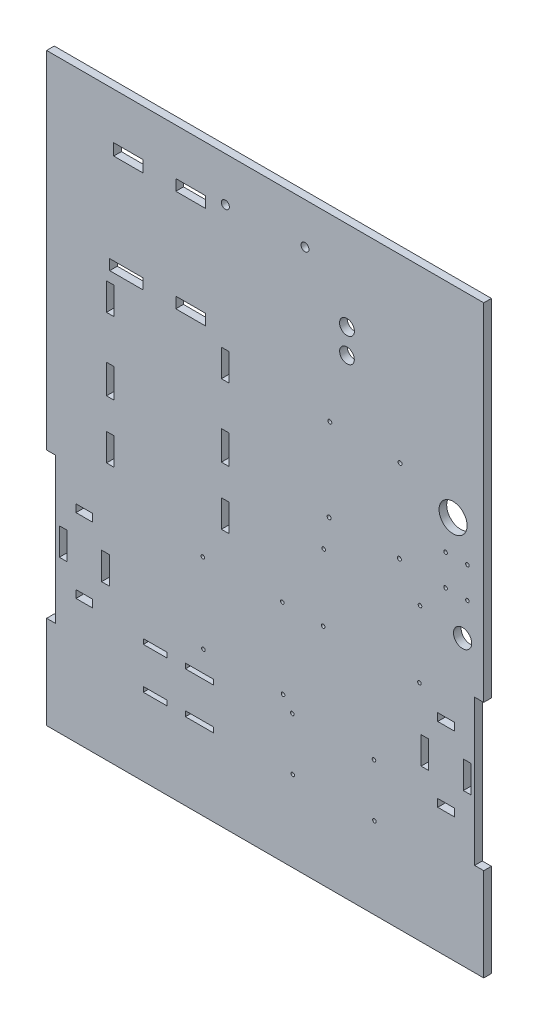
SolidWorks part; units mm, degrees
ref_plane "Front Plane" through (0, 0, 0) normal (0, 0, 1) x (1, 0, 0)
ref_plane "Top Plane" through (0, 0, 0) normal (0, 1, 0) x (1, 0, 0)
ref_plane "Right Plane" through (0, 0, 0) normal (1, 0, 0) x (0, 0, -1)
sketch "Sketch1" plane through (0, 0, 0) normal (0, 0, 1) x (1, 0, 0)
  line L1 (-152.4, 152.4) -> (152.4, 152.4)
  line L2 (-152.4, 152.4) -> (-152.4, -152.4)
  line L3 (-152.4, -152.4) -> (152.4, -152.4)
  line L4 (152.4, 152.4) -> (152.4, -152.4)
  line L5 (-152.4, 152.4) -> (152.4, -152.4) construction
  line L6 (-152.4, -152.4) -> (152.4, 152.4) construction
  point P0 (0, 0)
  dimension "D1" = 304.8
  dimension "D2" = 304.8
extrude "Boss-Extrude1" add sketch "Sketch1" along normal blind 5.334
sketch "Sketch2" plane through (0, 0, 0) normal (0, 0, -1) x (-1, 0, 0)
  line L0 (152.4, 152.4) -> (152.4, -152.4) construction
  line L1 (152.4, -12.7) -> (146.05, -12.7)
  line L2 (152.4, -12.7) -> (152.4, -114.3)
  line L3 (152.4, -114.3) -> (146.05, -114.3)
  line L4 (146.05, -12.7) -> (146.05, -114.3)
  line L5 (-152.4, -152.4) -> (-152.4, 152.4) construction
  line L6 (-152.4, -12.7) -> (-146.05, -12.7)
  line L7 (-152.4, -12.7) -> (-152.4, -114.3)
  line L8 (-152.4, -114.3) -> (-146.05, -114.3)
  line L9 (-146.05, -12.7) -> (-146.05, -114.3)
  line L10 (152.4, -152.4) -> (-152.4, -152.4) construction
  dimension "D1" = 101.6
  dimension "D2" = 101.6
  dimension "D3" = 38.1
  dimension "D4" = 38.1
  dimension "D5" = 6.35
  dimension "D6" = 6.35
extrude "Cut-Extrude1" cut sketch "Sketch2" against normal through all
sketch "Sketch26" plane through (0, 0, 5.334) normal (0, 0, 1) x (1, 0, 0)
  line L1 (-131.9107, -92.075) -> (-120.3113, -92.075)
  line L2 (-131.9107, -92.075) -> (-131.9107, -86.741)
  line L3 (-131.9107, -86.741) -> (-120.3113, -86.741)
  line L4 (-120.3113, -92.075) -> (-120.3113, -86.741)
  line L5 (-114.046, -73.025) -> (-108.712, -73.025)
  line L6 (-114.046, -73.025) -> (-114.046, -53.975)
  line L7 (-114.046, -53.975) -> (-108.712, -53.975)
  line L8 (-108.712, -73.025) -> (-108.712, -53.975)
  line L9 (-131.9107, -40.259) -> (-120.3113, -40.259)
  line L10 (-131.9107, -40.259) -> (-131.9107, -34.925)
  line L11 (-131.9107, -34.925) -> (-120.3113, -34.925)
  line L12 (-120.3113, -40.259) -> (-120.3113, -34.925)
  line L13 (-143.51, -73.025) -> (-138.176, -73.025)
  line L14 (-143.51, -73.025) -> (-143.51, -53.975)
  line L15 (-143.51, -53.975) -> (-138.176, -53.975)
  line L16 (-138.176, -73.025) -> (-138.176, -53.975)
extrude "Cut-Extrude11" cut sketch "Sketch26" against normal through all
sketch "Sketch27" plane through (0, 0, 5.334) normal (0, 0, 1) x (1, 0, 0)
  line L1 (131.9107, -92.075) -> (120.3113, -92.075)
  line L2 (131.9107, -92.075) -> (131.9107, -86.741)
  line L3 (131.9107, -86.741) -> (120.3113, -86.741)
  line L4 (120.3113, -92.075) -> (120.3113, -86.741)
  line L5 (114.046, -73.025) -> (108.712, -73.025)
  line L6 (114.046, -73.025) -> (114.046, -53.975)
  line L7 (114.046, -53.975) -> (108.712, -53.975)
  line L8 (108.712, -73.025) -> (108.712, -53.975)
  line L9 (131.9107, -40.259) -> (120.3113, -40.259)
  line L10 (131.9107, -40.259) -> (131.9107, -34.925)
  line L11 (131.9107, -34.925) -> (120.3113, -34.925)
  line L12 (120.3113, -40.259) -> (120.3113, -34.925)
  line L13 (143.51, -73.025) -> (138.176, -73.025)
  line L14 (143.51, -73.025) -> (143.51, -53.975)
  line L15 (143.51, -53.975) -> (138.176, -53.975)
  line L16 (138.176, -73.025) -> (138.176, -53.975)
extrude "Cut-Extrude12" cut sketch "Sketch27" against normal through all
sketch "Sketch29" plane through (0, 0, 0) normal (0, 0, -1) x (-1, 0, 0)
  line L0 (152.4, -114.3) -> (152.4, -152.4) construction
  line L1 (-152.4, -152.4) -> (152.4, -152.4)
  line L2 (-152.4, -152.4) -> (-152.4, -128.3152)
  line L3 (-152.4, -128.3152) -> (152.4, -128.3152)
  line L4 (152.4, -152.4) -> (152.4, -128.3152)
extrude "Cut-Extrude13" cut sketch "Sketch29" against normal through all
sketch "Sketch30" plane through (0, 0, 0) normal (0, 0, -1) x (-1, 0, 0)
  circle A0 centre (27.7607, 197.7649) radius 2.7781
  circle A1 centre (-27.7607, 199.9013) radius 2.7781
sketch "Sketch31" plane through (0, 0, 0) normal (0, 0, -1) x (-1, 0, 0)
  circle A0 centre (-94.0723, 102.6888) radius 1.375
  circle A1 centre (-45.0742, 103.1164) radius 1.375
  circle A2 centre (-93.5662, 44.691) radius 1.375
  circle A3 centre (-44.5681, 45.1186) radius 1.375
extrude "Cut-Extrude15" cut sketch "Sketch31" against normal through all
sketch "Sketch32" plane through (0, 0, 0) normal (0, 0, -1) x (-1, 0, 0)
  circle A0 centre (-125.7819, 64.7185) radius 1.25
  circle A1 centre (-141.0219, 64.7185) radius 1.25
  circle A2 centre (-141.0219, 43.1285) radius 1.25
  circle A3 centre (-125.7819, 43.1285) radius 1.25
extrude "Cut-Extrude16" cut sketch "Sketch32" against normal through all
sketch "Sketch34" plane through (0, 0, 0) normal (0, 0, -1) x (-1, 0, 0)
  circle A0 centre (-75.859, -85.6615) radius 1.2492
  circle A1 centre (-76.1788, -122.3001) radius 1.25
  circle A2 centre (-19.2207, -122.7972) radius 1.2525
  circle A3 centre (-18.9009, -86.1585) radius 1.252
extrude "Cut-Extrude18" cut sketch "Sketch34" against normal through all
sketch "Sketch38" plane through (0, 0, 0) normal (0, 0, -1) x (-1, 0, 0)
  circle A0 centre (43.525, -22.8195) radius 1.2482
  circle A1 centre (-11.9729, -22.3352) radius 1.2536
  circle A2 centre (-12.4572, -77.8331) radius 1.2525
  circle A3 centre (43.0406, -78.3174) radius 1.2379
extrude "Cut-Extrude22" cut sketch "Sketch38" against normal through all
sketch "Sketch40" plane through (0, 152.4, 0) normal (0, 1, 0) x (1, 0, 0)
  line L1 (152.4, -5.334) -> (-152.4, -5.334)
  line L2 (152.4, -5.334) -> (152.4, 0)
  line L3 (152.4, 0) -> (-152.4, 0)
  line L4 (-152.4, -5.334) -> (-152.4, 0)
extrude "Boss-Extrude2" add sketch "Sketch40" along normal blind 76.2
sketch "Sketch41" plane through (0, 0, 0) normal (0, 0, -1) x (-1, 0, 0)
  circle A1 centre (-27.7607, 199.9013) radius 2.7781
  circle A2 centre (27.7607, 197.7649) radius 2.7781
extrude "Cut-Extrude24" cut sketch "Sketch41" against normal through all
sketch "Sketch42" plane through (0, 0, 0) normal (0, 0, -1) x (-1, 0, 0)
  circle A0 centre (-40.4289, -22.6525) radius 1.2465
  circle A1 centre (-107.5463, -23.2383) radius 1.2519
  circle A2 centre (-107.9547, 23.56) radius 1.2487
  circle A3 centre (-40.8373, 24.1457) radius 1.2456
extrude "Cut-Extrude25" cut sketch "Sketch42" against normal through all and the other way through all
sketch "Sketch44" plane through (0, 0, 0) normal (0, 0, -1) x (-1, 0, 0)
  line L0 (8.1367, -121.7414) -> (109.7367, -121.7414) construction
  line L1 (84.9513, -121.7414) -> (68.4744, -121.7414)
  line L2 (84.9513, -121.7414) -> (84.9513, -125.2414)
  line L3 (84.9513, -125.2414) -> (68.4744, -125.2414)
  line L4 (68.4744, -121.7414) -> (68.4744, -125.2414)
  line L5 (8.1367, -96.3414) -> (109.7367, -96.3414) construction
  line L6 (84.9513, -96.3414) -> (68.4744, -96.3414)
  line L7 (84.9513, -96.3414) -> (84.9513, -92.8414)
  line L8 (84.9513, -92.8414) -> (68.4744, -92.8414)
  line L9 (68.4744, -96.3414) -> (68.4744, -92.8414)
  line L10 (55.5989, -121.7414) -> (55.5989, -96.3414) construction
  line L11 (55.5989, -121.7414) -> (35.9657, -121.7414)
  line L12 (55.5989, -121.7414) -> (55.5989, -125.3381)
  line L13 (55.5989, -125.3381) -> (35.9657, -125.3381)
  line L14 (35.9657, -121.7414) -> (35.9657, -125.3381)
  line L15 (55.5989, -96.4381) -> (35.9657, -96.4381)
  line L16 (55.5989, -96.4381) -> (55.5989, -92.9381)
  line L17 (55.5989, -92.9381) -> (35.9657, -92.9381)
  line L18 (35.9657, -96.4381) -> (35.9657, -92.9381)
  dimension "D1" = 3.5
  dimension "D2" = 3.5
extrude "Cut-Extrude27" cut sketch "Sketch44" against normal through all
sketch "Sketch45" plane through (0, 0, 0) normal (0, 0, -1) x (-1, 0, 0)
  line L0 (146.4593, 187.8495) -> (-21.8093, 189.318) construction
  line L1 (105.6204, 188.2059) -> (85.2662, 188.2059)
  line L2 (105.6204, 188.2059) -> (105.6204, 196.272)
  line L3 (105.6204, 196.272) -> (85.2662, 196.272)
  line L4 (85.2662, 188.2059) -> (85.2662, 196.272)
  line L5 (145.9051, 124.3519) -> (-22.3635, 125.8204) construction
  line L6 (62.325, 188.5838) -> (41.77, 188.5838)
  line L7 (62.325, 188.5838) -> (62.325, 196.272)
  line L8 (62.325, 196.272) -> (41.77, 196.272)
  line L9 (41.77, 188.5838) -> (41.77, 196.272)
  line L10 (41.77, 125.2607) -> (62.325, 125.2607)
  line L11 (41.77, 125.2607) -> (41.77, 117.6085)
  line L12 (41.77, 117.6085) -> (62.325, 117.6085)
  line L13 (62.325, 125.2607) -> (62.325, 117.6085)
  line L15 (85.2662, 124.8811) -> (108.4025, 124.8811)
  line L16 (85.2662, 124.8811) -> (85.2662, 117.6085)
  line L17 (85.2662, 117.6085) -> (108.4025, 117.6085)
  line L18 (108.4025, 124.8811) -> (108.4025, 117.6085)
extrude "Cut-Extrude28" cut sketch "Sketch45" against normal through all
sketch "Sketch46" plane through (0, -128.3152, 0) normal (0, -1, 0) x (1, 0, 0)
  line L1 (152.4, 0) -> (-152.4, 0)
  line L2 (152.4, 0) -> (152.4, 5.334)
  line L3 (152.4, 5.334) -> (-152.4, 5.334)
  line L4 (-152.4, 0) -> (-152.4, 5.334)
extrude "Boss-Extrude3" add sketch "Sketch46" along normal blind 50.8
sketch "Sketch47" plane through (0, 0, 0) normal (0, 0, -1) x (-1, 0, 0)
  circle A0 centre (-131.0175, 88.2122) radius 9.7785
  circle A1 centre (-137.651, 18.756) radius 6.3521
extrude "Cut-Extrude29" cut sketch "Sketch47" against normal through all
sketch "Sketch49" plane through (0, 0, 5.334) normal (0, 0, 1) x (1, 0, 0)
  line L1 (-25.1793, 0.3822) -> (-30.5133, 0.3822)
  line L2 (-25.1793, 0.3822) -> (-25.1793, 19.4322)
  line L3 (-25.1793, 19.4322) -> (-30.5133, 19.4322)
  line L4 (-30.5133, 0.3822) -> (-30.5133, 19.4322)
  line L5 (-105.3154, 0.3822) -> (-110.6494, 0.3822)
  line L6 (-105.3154, 0.3822) -> (-105.3154, 19.4322)
  line L7 (-105.3154, 19.4322) -> (-110.6494, 19.4322)
  line L8 (-110.6494, 0.3822) -> (-110.6494, 19.4322)
  line L9 (-105.3154, 40.9201) -> (-110.6494, 40.9201)
  line L10 (-105.3154, 40.9201) -> (-105.3154, 61.2159)
  line L11 (-105.3154, 61.2159) -> (-110.6494, 61.2159)
  line L12 (-110.6494, 40.9201) -> (-110.6494, 61.2159)
  line L13 (-105.3154, 91.3142) -> (-110.6494, 91.3142)
  line L14 (-105.3154, 91.3142) -> (-105.3154, 110.3642)
  line L15 (-105.3154, 110.3642) -> (-110.6494, 110.3642)
  line L16 (-110.6494, 91.3142) -> (-110.6494, 110.3642)
  line L17 (-25.1793, 91.3142) -> (-30.5133, 91.3142)
  line L18 (-25.1793, 91.3142) -> (-25.1793, 110.3642)
  line L19 (-25.1793, 110.3642) -> (-30.5133, 110.3642)
  line L20 (-30.5133, 91.3142) -> (-30.5133, 110.3642)
  line L21 (-25.1793, 40.9201) -> (-30.5133, 40.9201)
  line L22 (-25.1793, 40.9201) -> (-25.1793, 61.2159)
  line L23 (-25.1793, 61.2159) -> (-30.5133, 61.2159)
  line L24 (-30.5133, 40.9201) -> (-30.5133, 61.2159)
extrude "Cut-Extrude30" cut sketch "Sketch49" against normal through all
sketch "Sketch52" plane through (0, 0, 0) normal (0, 0, -1) x (-1, 0, 0)
  circle A0 centre (-57.0215, 149.1591) radius 5.1137
  circle A1 centre (-57.0215, 166.2995) radius 5.1779
extrude "Cut-Extrude33" cut sketch "Sketch52" against normal through all contours A1 | A0
equation "\"Mdf\"= .21in"
equation "\"Foamcore\"= .1875in"
equation "\"Gmaterial\"= \"Foamcore\""
equation "\"D1@Boss-Extrude1\" = \"Mdf\""
equation "\"D1@Boss-Extrude2\"=3in"
